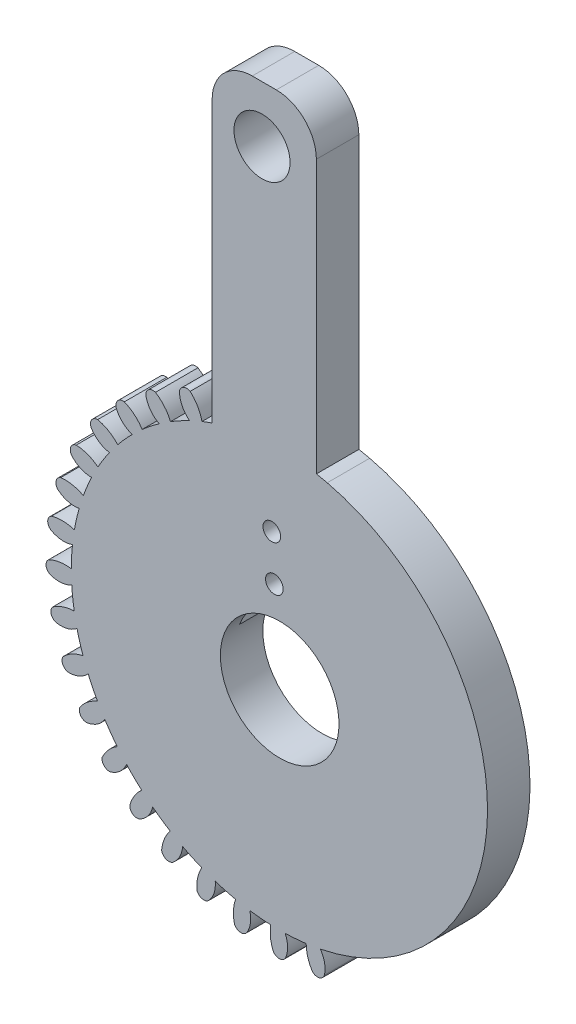
SolidWorks part; units mm, degrees
ref_plane "Front Plane" through (0, 0, 0) normal (0, 0, 1) x (1, 0, 0)
ref_plane "Top Plane" through (0, 0, 0) normal (0, 1, 0) x (1, 0, 0)
ref_plane "Right Plane" through (0, 0, 0) normal (1, 0, 0) x (0, 0, -1)
sketch "Sketch1" plane through (0, 0, 0) normal (0, 0, 1) x (1, 0, 0)
  circle A0 centre (0, 0) radius 13
extrude "Boss-Extrude1" add sketch "Sketch1" along normal blind 2.65
sketch "Sketch2" plane through (0, 0, 2.65) normal (0, 0, 1) x (1, 0, 0)
  line L0 (-1.4072, 12.9236) -> (-0.5647, 12.9877)
  arc A0 (-0.5647, 12.9877) -> (-0.8397, 14.4228) centre (-2.9593, 13.2728) ccw
  circle A1 centre (0, 0) radius 13 construction
  arc A2 (-0.8397, 14.4228) -> (-1.5928, 14.2987) centre (-1.1777, 14.1267) ccw
  arc A3 (-1.5928, 14.2987) -> (-1.4072, 12.9236) centre (-0.0609, 13.8053) ccw
extrude "Boss-Extrude2" add sketch "Sketch2" against normal blind 2.65
pattern_circular "CirPattern1" count 37 over 360 about axis through (-0.0032, 0.0389, 0) along (0, 0, 1) of "Boss-Extrude2"
sketch "Sketch3" plane through (0, 0, 2.65) normal (0, 0, 1) x (1, 0, 0)
  arc A0 (2.5398, -12.7495) -> (2.9649, 12.6574) centre (-0.0422, 0.0007) ccw
  arc A1 (3.036, -15.1997) -> (3.5428, 15.0897) centre (-0.0422, 0.0007) ccw
  arc A2 (2.5398, -12.7495) -> (3.036, -15.1997) centre (1.5628, -14.2227) cw
  arc A3 (3.5428, 15.0897) -> (2.9649, 12.6574) centre (4.47, 13.5846) ccw
  dimension "D1" = 2.5
extrude "Cut-Extrude1" cut sketch "Sketch3" against normal blind 6
sketch "Sketch5" plane through (0, 0, 2.65) normal (0, 0, 1) x (1, 0, 0)
  line L1 (-4.2117, 12.2988) -> (2.2883, 12.2988)
  line L2 (-4.2117, 12.2988) -> (-4.2117, 32.2988)
  line L3 (-4.2117, 32.2988) -> (2.2883, 32.2988)
  line L4 (2.2883, 12.2988) -> (2.2883, 32.2988)
  arc A0 (-3.5651, 12.5016) -> (-4.8468, 12.0627) centre (0, 0) ccw construction
  dimension "D1" = 20
  dimension "D2" = 6.5
extrude "Boss-Extrude3" add sketch "Sketch5" against normal blind 2.65
fillet "Fillet1" radius 2.5 2 edges at (2.2883, 32.2988, 1.325) (-4.2117, 32.2988, 1.325)
sketch "Sketch6" plane through (0, 0, 0) normal (0, 0, -1) x (-1, 0, 0)
  circle A0 centre (0, 0) radius 3.7
  dimension "D1" = 7.4
extrude "Cut-Extrude2" cut sketch "Sketch6" against normal through all contours A0
sketch "Sketch7" plane through (0, 0, 0) normal (0, 0, -1) x (-1, 0, 0)
  line L0 (3.4574, 1.3177) -> (2.9338, 10.4369)
  line L1 (-2.9157, 2.2779) -> (-1.1125, 11.4725)
  circle A1 centre (0, 0) radius 3.7 construction
  arc A4 (3.4574, 1.3177) -> (-2.9157, 2.2779) centre (0, 0) ccw
  arc A5 (-1.1125, 11.4725) -> (2.9338, 10.4369) centre (0.5783, 9.656) cw
  point P1 (-2.9157, 2.2779)
  point P8 (3.4574, 1.3177)
  point P9 (-1.1125, 11.4725)
  point P10 (2.9338, 10.4369)
sketch "Sketch8" plane through (0, 0, 0) normal (0, 0, -1) x (-1, 0, 0)
  line L0 (0.2117, 32.2988) -> (1.7117, 32.2988) construction
  circle A0 centre (1.1012, 28.7988) radius 1.75
  dimension "D1" = 3.5
  dimension "D2" = 3.5
extrude "Cut-Extrude4" cut sketch "Sketch8" against normal through all
extrude "Cut-Extrude5" cut sketch "Sketch7" against normal blind 1.7
sketch "Sketch9" plane through (0, 0, 1.7) normal (0, 0, -1) x (-1, 0, 0)
  circle A0 centre (0.3308, 5.5358) radius 0.55
  circle A1 centre (0.4908, 8.2944) radius 0.55
  point P4 (0.4908, 8.2944)
  point P5 (0.3308, 5.5358)
extrude "Cut-Extrude6" cut sketch "Sketch9" against normal through all
